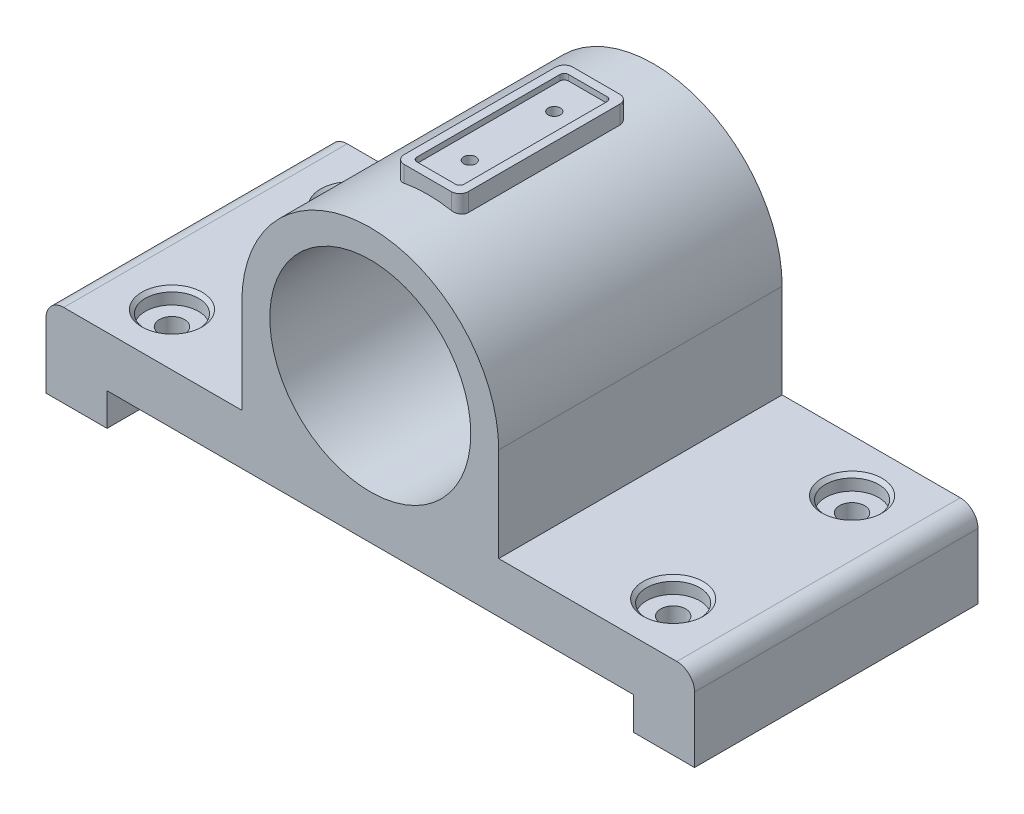
SolidWorks part; units mm, degrees
ref_plane "Front Plane" through (0, 0, 0) normal (0, 0, 1) x (1, 0, 0)
ref_plane "Top Plane" through (0, 0, 0) normal (0, 1, 0) x (1, 0, 0)
ref_plane "Right Plane" through (0, 0, 0) normal (1, 0, 0) x (0, 0, -1)
sketch "Sketch1" plane through (0, 0, 0) normal (0, 0, 1) x (1, 0, 0)
  line L0 (81.1319, 9.0401) -> (113.0575, 9.0401)
  line L1 (10.9414, 0) -> (105.2911, 0)
  line L2 (0, 0) -> (0, 5.8651)
  line L3 (3.175, 9.0401) -> (35.1006, 9.0401)
  line L4 (116.2325, 0) -> (116.2325, 5.8651)
  line L5 (81.1319, 25.9005) -> (81.1319, 9.0401)
  line L6 (35.1006, 25.9005) -> (35.1006, 9.0401)
  line L7 (58.1163, 25.9005) -> (58.1163, 63.1246) construction
  line L8 (116.2325, 0) -> (116.2325, -5.8495)
  line L9 (0, 0) -> (0, -5.8495)
  line L10 (0, -5.8495) -> (10.9414, -5.8495)
  line L11 (10.9414, 0) -> (10.9414, -5.8495)
  line L12 (105.2911, 0) -> (105.2911, -5.8495)
  line L13 (116.2325, -5.8495) -> (105.2911, -5.8495)
  arc A0 (81.1319, 25.9005) -> (35.1006, 25.9005) centre (58.1163, 25.9005) ccw
  arc A1 (3.175, 9.0401) -> (0, 5.8651) centre (3.175, 5.8651) ccw
  arc A2 (113.0575, 9.0401) -> (116.2325, 5.8651) centre (113.0575, 5.8651) cw
  circle A3 centre (58.1163, 25.9005) radius 18.0097
extrude "Extrude1" add sketch "Sketch1" against normal blind 50.8
ref_plane "Plane1" through (58.1163, 48.9161, 0) normal (0, 1, 0) x (-1, 0, 0)
ref_plane "Plane2" through (0, 51.4561, 0) normal (0, 1, 0) x (-1, 0, 0)
sketch "Sketch2" plane through (0, 51.4561, 0) normal (0, 1, 0) x (-1, 0, 0)
  line L0 (-58.1163, 0) -> (-58.1163, -50.8) construction
  line L1 (-35.1006, 0) -> (-81.1319, 0) construction
  line L2 (-81.1319, -50.8) -> (-35.1006, -50.8) construction
  line L4 (-62.3371, -10.2952) -> (-53.8954, -10.2952)
  line L5 (-63.8611, -11.8192) -> (-63.8611, -38.9808)
  line L6 (-62.3371, -40.5048) -> (-53.8954, -40.5048)
  line L7 (-52.3714, -11.8192) -> (-52.3714, -38.9808)
  arc A0 (-62.3371, -10.2952) -> (-63.8611, -11.8192) centre (-62.3371, -11.8192) ccw
  arc A1 (-52.3714, -11.8192) -> (-53.8954, -10.2952) centre (-53.8954, -11.8192) ccw
  arc A2 (-52.3714, -38.9808) -> (-53.8954, -40.5048) centre (-53.8954, -38.9808) cw
  arc A3 (-63.8611, -38.9808) -> (-62.3371, -40.5048) centre (-62.3371, -38.9808) ccw
  point P6 (-58.1163, -25.4)
  dimension "D1" = 1.524
extrude "Extrude2" add sketch "Sketch2" against normal up to body
sketch "Sketch3" plane through (0, 51.4561, 0) normal (0, 1, 0) x (-1, 0, 0)
  line L0 (-54.6574, -11.8192) -> (-61.5751, -11.8192)
  line L1 (-62.3371, -12.5812) -> (-62.3371, -38.2188)
  line L2 (-61.5751, -38.9808) -> (-54.6574, -38.9808)
  line L3 (-53.8954, -38.2188) -> (-53.8954, -12.5812)
  line L4 (-63.8611, -11.8192) -> (-63.8611, -38.9808)
  line L5 (-62.3371, -40.5048) -> (-53.8954, -40.5048)
  line L6 (-52.3714, -38.9808) -> (-52.3714, -11.8192)
  line L7 (-53.8954, -10.2952) -> (-62.3371, -10.2952)
  line L8 (-63.8611, -11.8192) -> (-63.8611, -38.9808)
  line L9 (-62.3371, -40.5048) -> (-53.8954, -40.5048)
  line L10 (-52.3714, -38.9808) -> (-52.3714, -11.8192)
  line L11 (-53.8954, -10.2952) -> (-62.3371, -10.2952)
  line L12 (-53.8954, -11.8192) -> (-62.3371, -11.8192) construction
  line L13 (-62.3371, -11.8192) -> (-62.3371, -38.9808) construction
  line L14 (-53.8954, -38.9808) -> (-53.8954, -11.8192) construction
  line L15 (-62.3371, -38.9808) -> (-53.8954, -38.9808) construction
  arc A0 (-53.8954, -12.5812) -> (-54.6574, -11.8192) centre (-54.6574, -12.5812) ccw
  arc A1 (-53.8954, -38.2188) -> (-54.6574, -38.9808) centre (-54.6574, -38.2188) cw
  arc A3 (-61.5751, -38.9808) -> (-62.3371, -38.2188) centre (-61.5751, -38.2188) cw
  arc A4 (-62.3371, -10.2952) -> (-63.8611, -11.8192) centre (-62.3371, -11.8192) ccw
  arc A5 (-63.8611, -38.9808) -> (-62.3371, -40.5048) centre (-62.3371, -38.9808) ccw
  arc A6 (-53.8954, -40.5048) -> (-52.3714, -38.9808) centre (-53.8954, -38.9808) ccw
  arc A7 (-52.3714, -11.8192) -> (-53.8954, -10.2952) centre (-53.8954, -11.8192) ccw
  arc A8 (-62.3371, -10.2952) -> (-63.8611, -11.8192) centre (-62.3371, -11.8192) ccw
  arc A9 (-63.8611, -38.9808) -> (-62.3371, -40.5048) centre (-62.3371, -38.9808) ccw
  arc A10 (-53.8954, -40.5048) -> (-52.3714, -38.9808) centre (-53.8954, -38.9808) ccw
  arc A11 (-52.3714, -11.8192) -> (-53.8954, -10.2952) centre (-53.8954, -11.8192) ccw
  arc A12 (-61.5751, -11.8192) -> (-62.3371, -12.5812) centre (-61.5751, -12.5812) ccw
  arc A13 (-62.3371, -11.8192) -> (-62.3371, -11.8192) centre (-62.3371, -11.8192) ccw construction
  arc A14 (-53.8954, -11.8192) -> (-53.8954, -11.8192) centre (-53.8954, -11.8192) ccw construction
  arc A15 (-62.3371, -38.9808) -> (-62.3371, -38.9808) centre (-62.3371, -38.9808) ccw construction
  arc A16 (-53.8954, -38.9808) -> (-53.8954, -38.9808) centre (-53.8954, -38.9808) ccw construction
  dimension "D3" = 0.762
  dimension "D1" = 0
  dimension "D2" = 1.524
extrude "Extrude3" cut sketch "Sketch3" against normal blind 1.016 flip side to cut
ref_plane "Plane3" through (0, 50.4401, 0) normal (0, 1, 0) x (-1, 0, 0)
sketch "Sketch4" plane through (0, 50.4401, 0) normal (0, 1, 0) x (-1, 0, 0)
  line L3 (-62.3371, -17.8256) -> (-58.1163, -17.8256) construction
  line L4 (-62.3371, -12.5812) -> (-62.3371, -38.2188) construction
  line L7 (-62.3371, -32.9744) -> (-58.1163, -32.9744) construction
hole_wizard "#2-64 Tapped Hole1" positions "Sketch6" profile "Sketch5" tap size "#2-64" standard "Ansi Inch"
sketch "Sketch6" plane through (0, 50.4401, 0) normal (0, 1, 0) x (-1, 0, 0)
  point P0 (-58.1163, -17.8256)
  point P1 (-58.1163, -32.9744)
sketch "Sketch5" plane through (58.1163, 50.4401, -17.8256) normal (1, 0, 0) x (0, 0, 1)
  line L0 (0, 0) -> (0, 6.1222)
  line L1 (0, 6.1222) -> (0.889, 5.588)
  line L2 (0.889, 5.588) -> (0.889, 4.318)
  line L3 (0.889, 4.318) -> (1.0922, 4.318)
  line L4 (1.0922, 4.318) -> (1.0922, 0)
  line L5 (1.0922, 0) -> (0, 0)
  line L10 (0, 6.1222) -> (-0.889, 5.588) construction
  line L11 (0, -6.35) -> (0, 107.95) construction
  dimension "Tap Drill Dia." = 1.778
  dimension "Tap Drill Depth" = 5.588
  dimension "Thread Major Dia." = 2.1844
  dimension "Thread Depth" = 4.318
  dimension "Drill Angle" = 118
ref_plane "Plane4" through (0, 9.0401, 0) normal (0, 1, 0) x (-1, 0, 0)
sketch "Sketch7" plane through (0, 9.0401, 0) normal (0, 1, 0) x (-1, 0, 0)
  line L3 (-113.0575, -41.4272) -> (-103.0313, -41.4272) construction
  line L4 (-113.0575, -50.8) -> (-113.0575, 0) construction
  line L6 (-113.0575, -9.3728) -> (-103.0313, -9.3728) construction
  line L8 (-3.175, -41.4272) -> (-13.2012, -41.4272) construction
  line L9 (-3.175, -9.3728) -> (-13.2012, -9.3728) construction
hole_wizard "CBORE for #8 Binding Head Machine Screw1" positions "Sketch9" profile "Sketch8" counterbore size "#8" standard "Ansi Inch" end condition through all
sketch "Sketch9" plane through (0, 9.0401, 0) normal (0, 1, 0) x (-1, 0, 0)
  point P0 (-103.0313, -9.3728)
  point P1 (-103.0313, -41.4272)
  point P3 (-13.2012, -9.3728)
  point P5 (-13.2012, -41.4272)
sketch "Sketch8" plane through (103.0313, 9.0401, -9.3728) normal (1, 0, 0) x (0, 0, 1)
  line L0 (0, 0) -> (0, 14.8897)
  line L1 (0, 14.8897) -> (2.2479, 14.8897)
  line L3 (2.2479, 14.8897) -> (2.2479, 2.667)
  line L4 (4.7625, 2.667) -> (2.2479, 2.667)
  line L5 (4.7625, 2.667) -> (4.7625, 0.635)
  line L6 (4.7625, 0.635) -> (5.3975, 0)
  line L7 (5.3975, 0) -> (0, 0)
  line L8 (-4.7625, 0.635) -> (-5.3975, 0) construction
  line L11 (0, -6.35) -> (0, 107.95) construction
  dimension "Thru Hole Dia." = 4.4958
  dimension "Thru Hole Depth" = 14.8897
  dimension "C'Bore Dia." = 9.525
  dimension "C'Bore Depth" = 2.667
  dimension "Near C'Sink Dia." = 10.795
  dimension "Near C'Sink Angle" = 90
